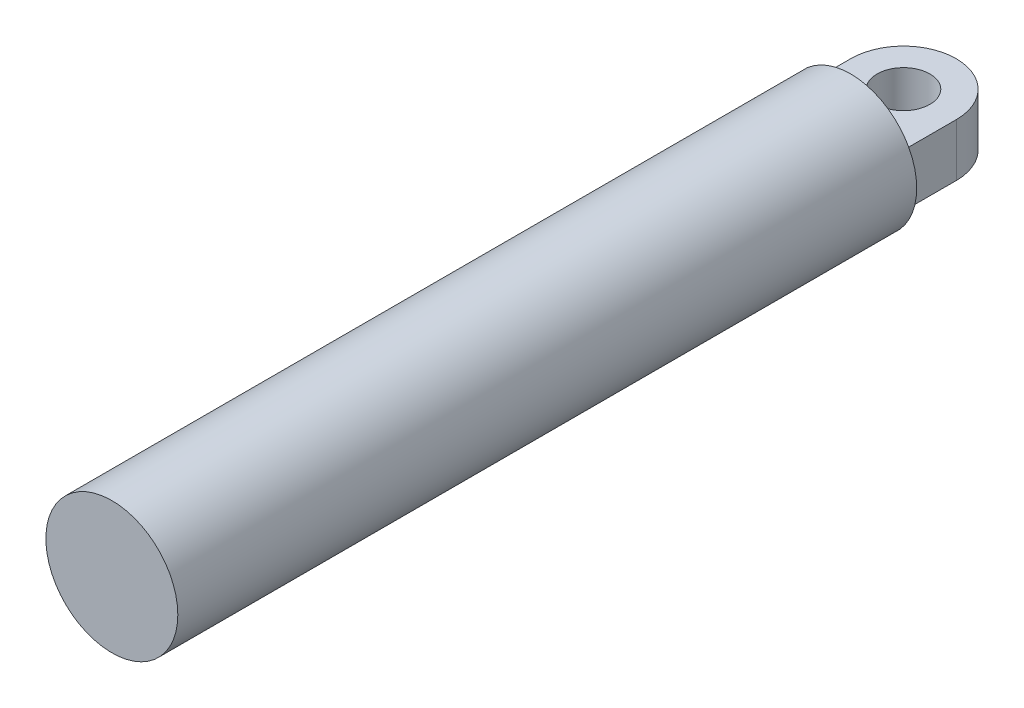
SolidWorks part; units mm, degrees
ref_plane "정면" through (0, 0, 0) normal (0, 0, 1) x (1, 0, 0)
ref_plane "윗면" through (0, 0, 0) normal (0, 1, 0) x (1, 0, 0)
ref_plane "우측면" through (0, 0, 0) normal (1, 0, 0) x (0, 0, -1)
sketch "스케치1" plane through (0, 0, 0) normal (0, 0, 1) x (1, 0, 0)
  circle A0 centre (0, 0) radius 25
  dimension "D1" = 50
extrude "보스-돌출1" add sketch "스케치1" against normal blind 30
sketch "스케치2" plane through (0, 0, -30) normal (0, 0, -1) x (-1, 0, 0)
  circle A1 centre (0, 0) radius 25
  dimension "D1" = 50
extrude "보스-돌출2" add sketch "스케치2" along normal blind 250
sketch "스케치3" plane through (0, 0, -280) normal (0, 0, -1) x (-1, 0, 0)
  line L0 (35, 0) -> (-35, 0)
  line L2 (-20, 10) -> (20, 10)
  line L3 (-20, 10) -> (-20, -10)
  line L4 (-20, -10) -> (20, -10)
  line L5 (20, 10) -> (20, -10)
  line L6 (-20, 10) -> (20, -10) construction
  line L7 (-20, -10) -> (20, 10) construction
  circle A0 centre (0, 0) radius 35
  dimension "D1" = 70
  dimension "D2" = 20
  dimension "D3" = 40
extrude "보스-돌출4" add sketch "스케치3" along normal blind 40 contours L5 L0 L3 L4 | L5 L2 L3 L0
sketch "스케치6" plane through (0, 10, 0) normal (0, 1, 0) x (1, 0, 0)
  line L0 (0, 320) -> (0, 280)
  line L1 (20, 320) -> (-20, 320) construction
  line L2 (20, 280) -> (-20, 280) construction
  circle A0 centre (0, 300) radius 20
  line M2 (20, 280) -> (20, 320)
  line M3 (20, 320) -> (-20, 320)
  line M4 (-20, 320) -> (-20, 280)
extrude "컷-돌출1" cut sketch "스케치6" against normal through all both and the other way through all contours A0 M3 M4 | A0 M2 M3
sketch "스케치7" plane through (0, 10, 0) normal (0, 1, 0) x (1, 0, 0)
  circle A0 centre (0, 300) radius 10
  dimension "D1" = 20
extrude "컷-돌출2" cut sketch "스케치7" against normal through all both and the other way through all
